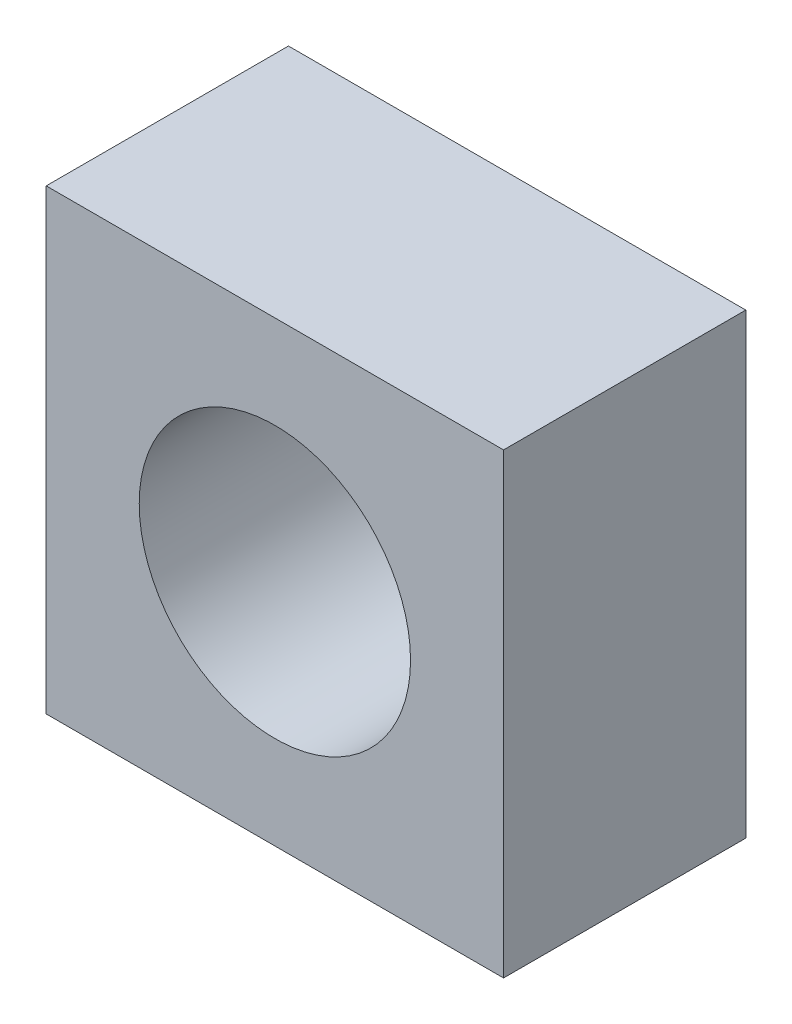
SolidWorks part; units mm, degrees
ref_plane "Front Plane" through (0, 0, 0) normal (0, 0, 1) x (1, 0, 0)
ref_plane "Top Plane" through (0, 0, 0) normal (0, 1, 0) x (1, 0, 0)
ref_plane "Right Plane" through (0, 0, 0) normal (1, 0, 0) x (0, 0, -1)
sketch "Sketch1" plane through (0, 0, 0) normal (0, 0, 1) x (1, 0, 0)
  line L1 (2.9972, -2.9972) -> (-2.9972, -2.9972)
  line L2 (2.9972, -2.9972) -> (2.9972, 2.9972)
  line L3 (2.9972, 2.9972) -> (-2.9972, 2.9972)
  line L4 (-2.9972, -2.9972) -> (-2.9972, 2.9972)
  line L5 (2.9972, -2.9972) -> (-2.9972, 2.9972) construction
  line L6 (2.9972, 2.9972) -> (-2.9972, -2.9972) construction
  point P0 (0, 0)
  dimension "D1" = 5.9944
  dimension "D2" = 5.9944
extrude "Boss-Extrude1" add sketch "Sketch1" along normal blind 3.175
sketch "Sketch2" plane through (0, 0, 3.175) normal (0, 0, 1) x (1, 0, 0)
  circle A0 centre (0, 0) radius 1.778
  dimension "D1" = 3.556
extrude "Cut-Extrude1" cut sketch "Sketch2" against normal blind 3.175
